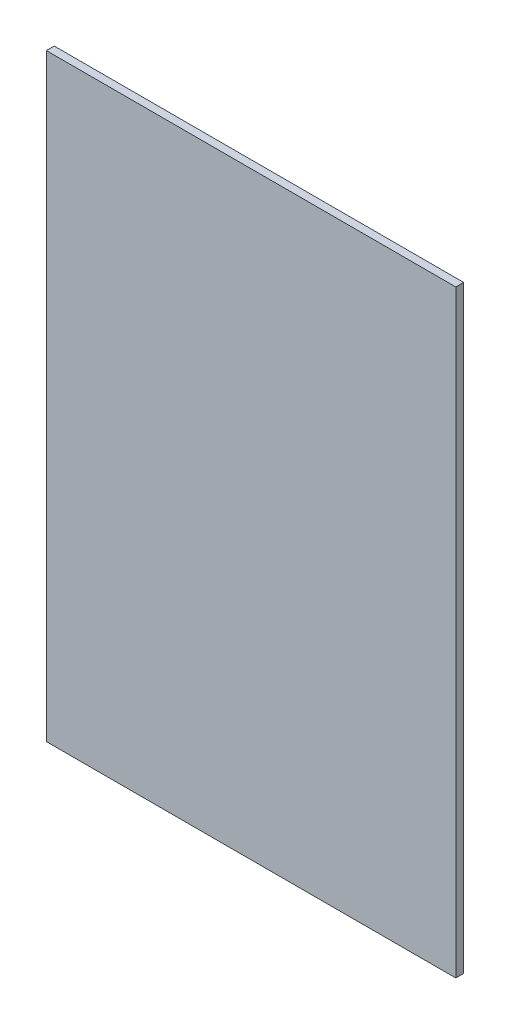
SolidWorks part; units mm, degrees
ref_plane "Front Plane" through (0, 0, 0) normal (0, 0, 1) x (1, 0, 0)
ref_plane "Top Plane" through (0, 0, 0) normal (0, 1, 0) x (1, 0, 0)
ref_plane "Right Plane" through (0, 0, 0) normal (1, 0, 0) x (0, 0, -1)
sketch "Sketch1" plane through (0, 0, 0) normal (0, 0, 1) x (1, 0, 0)
  line L1 (-130, 190) -> (130, 190)
  line L2 (-130, 190) -> (-130, -190)
  line L3 (-130, -190) -> (130, -190)
  line L4 (130, 190) -> (130, -190)
  line L5 (-130, 190) -> (130, -190) construction
  line L6 (-130, -190) -> (130, 190) construction
  point P0 (0, 0)
  dimension "D1" = 380
  dimension "D2" = 260
extrude "Boss-Extrude1" add sketch "Sketch1" along normal mid plane 5
